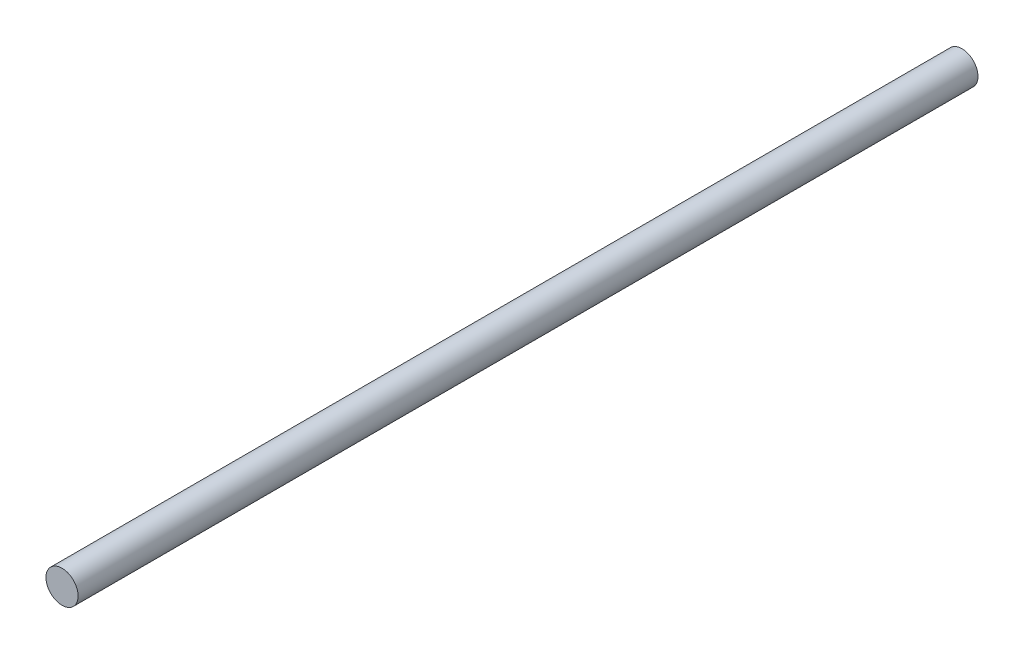
SolidWorks part; units mm, degrees
ref_plane "Спереди" through (0, 0, 0) normal (0, 0, 1) x (1, 0, 0)
ref_plane "Сверху" through (0, 0, 0) normal (0, 1, 0) x (1, 0, 0)
ref_plane "Справа" through (0, 0, 0) normal (1, 0, 0) x (0, 0, -1)
sketch "Эскиз1" plane through (0, 0, 0) normal (0, 0, 1) x (1, 0, 0)
  circle A0 centre (0, 0) radius 12.5
  point P2 (0, 0)
  dimension "D1" = 25
extrude "Бобышка-Вытянуть1" add sketch "Эскиз1" along normal blind 700
